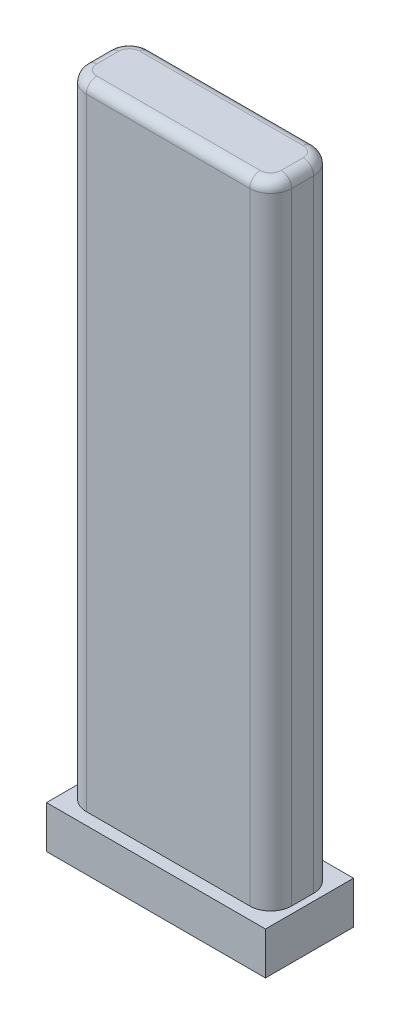
SolidWorks part; units mm, degrees
ref_plane "Front Plane" through (0, 0, 0) normal (0, 0, 1) x (1, 0, 0)
ref_plane "Top Plane" through (0, 0, 0) normal (0, 1, 0) x (1, 0, 0)
ref_plane "Right Plane" through (0, 0, 0) normal (1, 0, 0) x (0, 0, -1)
sketch "Sketch1" plane through (0, 0, 0) normal (0, 1, 0) x (1, 0, 0)
  line L1 (-7.8, 3.05) -> (7.8, 3.05)
  line L2 (-9.8, 1.05) -> (-9.8, -1.05)
  line L3 (-7.8, -3.05) -> (7.8, -3.05)
  line L4 (9.8, 1.05) -> (9.8, -1.05)
  line L5 (-9.8, 3.05) -> (9.8, -3.05) construction
  line L6 (-9.8, -3.05) -> (9.8, 3.05) construction
  arc A0 (7.8, -3.05) -> (9.8, -1.05) centre (7.8, -1.05) ccw
  arc A1 (7.8, 3.05) -> (9.8, 1.05) centre (7.8, 1.05) cw
  arc A2 (-7.8, 3.05) -> (-9.8, 1.05) centre (-7.8, 1.05) ccw
  arc A3 (-9.8, -1.05) -> (-7.8, -3.05) centre (-7.8, -1.05) ccw
  point P0 (0, 0)
  dimension "D3" = 2
  dimension "D1" = 6.1
  dimension "D2" = 19.6
extrude "Boss-Extrude1" add sketch "Sketch1" along normal blind 60.3
sketch "Sketch2" plane through (0, 0, 0) normal (0, 1, 0) x (1, 0, 0)
  line L0 (7.8, 3.05) -> (-7.8, 3.05) construction
  line L1 (-10.45, 4.2) -> (10.45, 4.2)
  line L2 (-10.45, 4.2) -> (-10.45, -4.2)
  line L3 (-10.45, -4.2) -> (10.45, -4.2)
  line L4 (10.45, 4.2) -> (10.45, -4.2)
  line L5 (-10.45, 4.2) -> (10.45, -4.2) construction
  line L6 (-10.45, -4.2) -> (10.45, 4.2) construction
  line L7 (-9.8, 1.05) -> (-9.8, -1.05) construction
  point P0 (0, 0)
  dimension "D1" = 1.15
  dimension "D2" = 0.65
  dimension "D3" = 10.45
extrude "Boss-Extrude2" add sketch "Sketch2" against normal blind 4.55
fillet "Fillet1" radius 1 8 edges at (-9.2142, 60.3, 2.4642) (-9.8, 60.3, 0) (-9.2142, 60.3, -2.4642) (0, 60.3, -3.05) (9.2142, 60.3, -2.4642) (9.8, 60.3, 0) (9.2142, 60.3, 2.4642) (0, 60.3, 3.05)
chamfer "Chamfer1" distance 0.5 angle 45 4 edges at (-10.45, -4.55, 0) (0, -4.55, -4.2) (10.45, -4.55, 0) (0, -4.55, 4.2)
